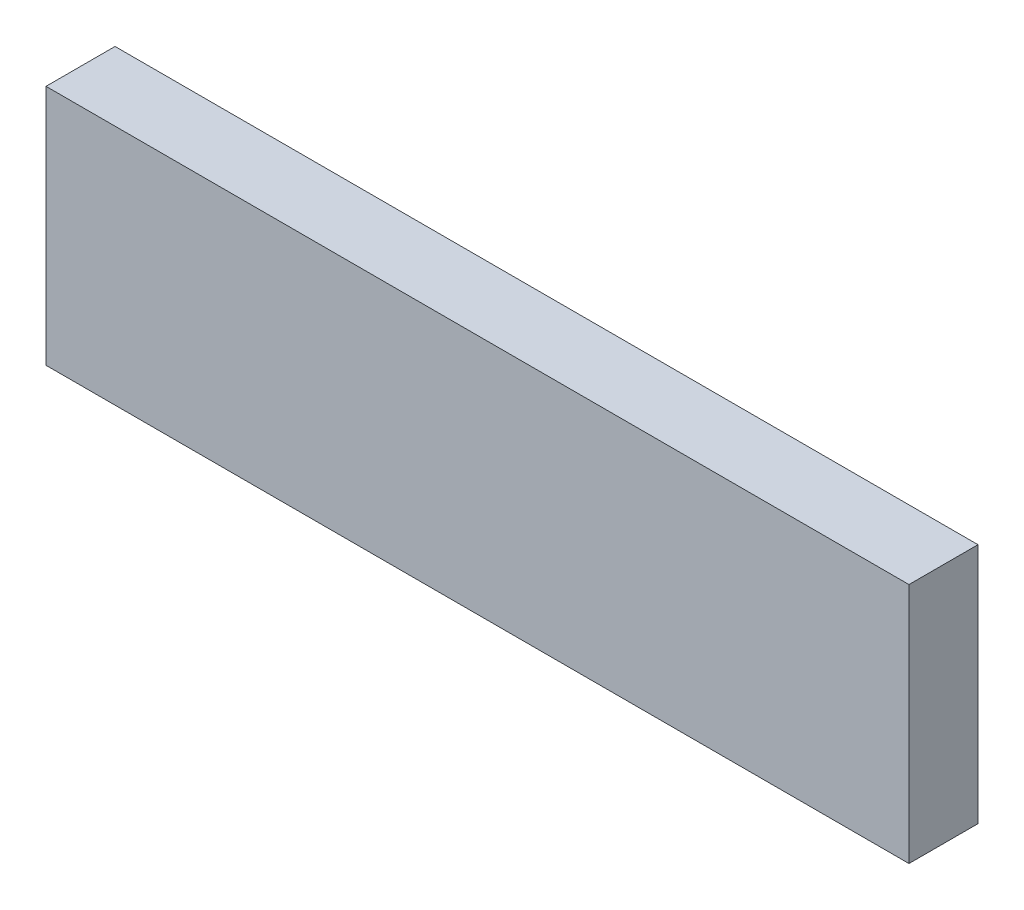
SolidWorks part; units mm, degrees
ref_plane "前视基准面" through (0, 0, 0) normal (0, 0, 1) x (1, 0, 0)
ref_plane "上视基准面" through (0, 0, 0) normal (0, 1, 0) x (1, 0, 0)
ref_plane "右视基准面" through (0, 0, 0) normal (1, 0, 0) x (0, 0, -1)
other "Configuration Table"
sketch "草图1" plane through (0, 0, 0) normal (0, 0, 1) x (1, 0, 0)
  line L1 (-125, -35) -> (125, -35)
  line L2 (-125, -35) -> (-125, 35)
  line L3 (-125, 35) -> (125, 35)
  line L4 (125, -35) -> (125, 35)
  line L5 (-125, -35) -> (125, 35) construction
  line L6 (-125, 35) -> (125, -35) construction
  point P0 (0, 0)
extrude "凸台-拉伸1" add sketch "草图1" along normal blind 20
